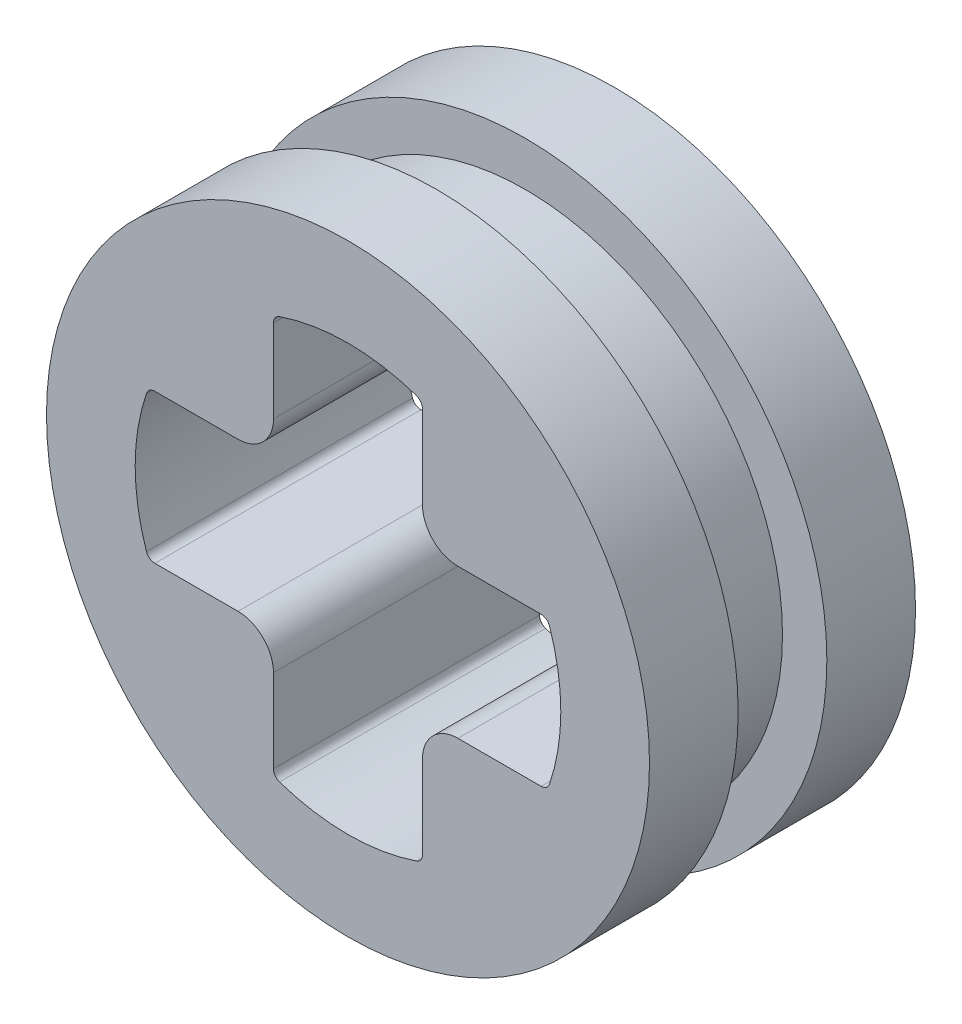
SolidWorks part; units mm, degrees
ref_plane "Front Plane" through (0, 0, 0) normal (0, 0, 1) x (1, 0, 0)
ref_plane "Top Plane" through (0, 0, 0) normal (0, 1, 0) x (1, 0, 0)
ref_plane "Right Plane" through (0, 0, 0) normal (1, 0, 0) x (0, 0, -1)
sketch "Sketch1" plane through (0, 0, 0) normal (0, 0, 1) x (1, 0, 0)
  circle A1 centre (0, 0) radius 3.4
  dimension "D2" = 6.8
extrude "Boss-Extrude1" add sketch "Sketch1" along normal blind 1
sketch "Sketch2" plane through (0, 0, 1) normal (0, 0, 1) x (1, 0, 0)
  circle A0 centre (0, 0) radius 2.9
  dimension "D1" = 5.8
extrude "Boss-Extrude2" add sketch "Sketch2" along normal blind 1
ref_plane "Plane1" through (0, 0, 1.5) normal (0, 0, 1) x (1, 0, 0)
mirror "Mirror3" about plane through (0, 0, 1.5) normal (0, 0, 1) of "Boss-Extrude1"
sketch "Sketch3" plane through (0, 0, 0) normal (0, 0, -1) x (-1, 0, 0)
  line L0 (0.84, -0.84) -> (0.84, -2.2482)
  line L2 (-0.84, 2.2482) -> (-0.84, 0.84)
  line L4 (0.84, 2.2482) -> (0.84, 0.84)
  line L5 (-0.84, 2.2482) -> (0.84, -2.2482) construction
  line L6 (-0.84, -2.2482) -> (0.84, 2.2482) construction
  line L7 (-2.2482, 0.84) -> (-0.84, 0.84)
  line L9 (-2.2482, -0.84) -> (-0.84, -0.84)
  line L11 (-2.2482, 0.84) -> (2.2482, -0.84) construction
  line L12 (-2.2482, -0.84) -> (2.2482, 0.84) construction
  line L13 (-0.84, -0.84) -> (-0.84, -2.2482)
  line L14 (0.84, 0.84) -> (2.2482, 0.84)
  line L15 (0.84, -0.84) -> (2.2482, -0.84)
  arc A0 (-2.2482, 0.84) -> (-2.2482, -0.84) centre (0, 0) ccw
  arc A1 (0.84, 2.2482) -> (-0.84, 2.2482) centre (0, 0) ccw
  arc A2 (2.2482, -0.84) -> (2.2482, 0.84) centre (0, 0) ccw
  arc A3 (-0.84, -2.2482) -> (0.84, -2.2482) centre (0, 0) ccw
  dimension "D1" = 4.8
  dimension "D2" = 1.68
  dimension "D3" = 1.68
extrude "Cut-Extrude1" cut sketch "Sketch3" against normal through all
fillet "Fillet1" radius 0.4 1 edges at (-0.84, 0.84, 1.5)
fillet "Fillet2" radius 0.4 1 edges at (0.84, 0.84, 1.5)
fillet "Fillet3" radius 0.4 1 edges at (0.84, -0.84, 1.5)
fillet "Fillet4" radius 0.4 1 edges at (-0.84, -0.84, 1.5)
fillet "Fillet5" radius 0.1 1 edges at (0.84, -2.2482, 1.5)
fillet "Fillet6" radius 0.1 1 edges at (-0.84, -2.2482, 1.5)
fillet "Fillet7" radius 0.1 1 edges at (-2.2482, 0.84, 1.5)
fillet "Fillet8" radius 0.1 1 edges at (-2.2482, -0.84, 1.5)
fillet "Fillet9" radius 0.1 1 edges at (-0.84, 2.2482, 1.5)
fillet "Fillet10" radius 0.1 1 edges at (0.84, 2.2482, 1.5)
fillet "Fillet11" radius 0.1 1 edges at (2.2482, 0.84, 1.5)
fillet "Fillet12" radius 0.1 1 edges at (2.2482, -0.84, 1.5)
